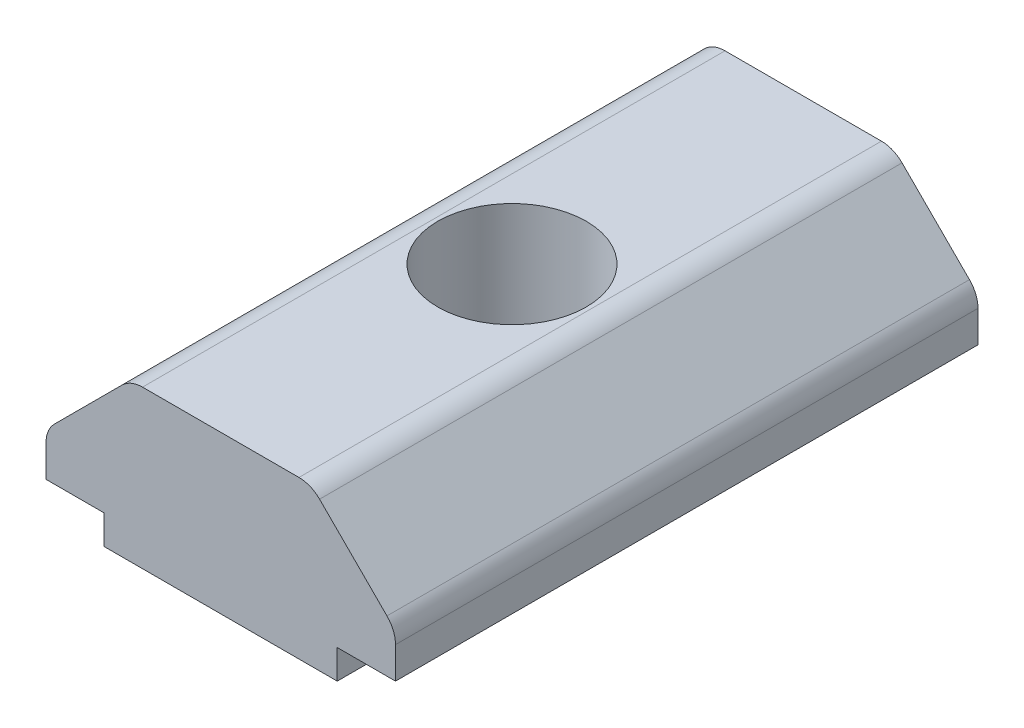
SolidWorks part; units mm, degrees
ref_plane "Front Plane" through (0, 0, 0) normal (0, 0, 1) x (1, 0, 0)
ref_plane "Top Plane" through (0, 0, 0) normal (0, 1, 0) x (1, 0, 0)
ref_plane "Right Plane" through (0, 0, 0) normal (1, 0, 0) x (0, 0, -1)
sketch "Sketch1" plane through (0, 0, 0) normal (0, 0, 1) x (1, 0, 0)
  line L0 (0, 0) -> (8, 0)
  line L1 (8, 0) -> (8, 1)
  line L2 (8, 1) -> (10, 1)
  line L3 (10, 1) -> (10, 2.5)
  line L4 (10, 2.5) -> (7.1, 5.4)
  line L5 (7.1, 5.4) -> (0.9, 5.4)
  line L6 (0.9, 5.4) -> (-2, 2.5)
  line L7 (-2, 2.5) -> (-2, 1)
  line L8 (-2, 1) -> (0, 1)
  line L9 (0, 1) -> (0, 0)
  line L10 (4, 5.4) -> (4, 0) construction
  dimension "D1" = 8
  dimension "D2" = 12
  dimension "D3" = 5.4
  dimension "D4" = 1
  dimension "D5" = 1.5
extrude "Extrude1" add sketch "Sketch1" along normal blind 20
fillet "Fillet1" radius 1 4 edges at (-2, 2.5, 10) (10, 2.5, 10) (0.9, 5.4, 10) (7.1, 5.4, 10)
sketch "Sketch2" plane through (0, 5.4, 0) normal (0, 1, 0) x (1, 0, 0)
  line L0 (4, -20) -> (4, 0) construction
  line L1 (6.6858, -20) -> (1.3142, -20) construction
  line L2 (6.6858, 0) -> (1.3142, 0) construction
  circle A0 centre (4, -10) radius 2.55
  dimension "D1" = 5.1
extrude "Extrude2" cut sketch "Sketch2" against normal through all
sketch "Sketch3" [suppressed] plane through (0, 5.4, 0) normal (0, 1, 0) x (1, 0, 0)
  line L0 (1.3142, -10) -> (6.6858, -10) construction
  line L1 (1.3142, 0) -> (1.3142, -20) construction
  line L2 (6.6858, -20) -> (6.6858, 0) construction
  line L3 (4, -15) -> (4, -10) construction
  circle A0 centre (4, -15) radius 3
  circle A1 centre (4, -5) radius 3
  dimension "D1" = 6
  dimension "D2" = 10
extrude "Extrude3" [suppressed] cut sketch "Sketch3" against normal through all
hole_wizard "M6 Clearance Hole1" [suppressed] positions "3DSketch1" profile "Sketch4" hole size "M6" standard "DIN"
sketch3d "3DSketch1"
  line L0 (4, 0, 20) -> (4, 0, 0) construction
  line L1 (0, 0, 20) -> (8, 0, 20) construction
  line L2 (0, 0, 0) -> (8, 0, 0) construction
  point P0 (4, 0, 10)
sketch "Sketch4" plane through (4, 0, 10) normal (1, 0, 0) x (0, 0, -1)
  line L0 (0, 0) -> (0, 5.4)
  line L1 (0, 5.4) -> (3.3, 5.4)
  line L2 (3.3, 5.4) -> (3.3, 0)
  line L5 (3.3, 0) -> (0, 0)
  line L11 (0, -6.35) -> (0, 107.95) construction
  dimension "Thru Hole Dia." = 6.6
  dimension "Thru Hole Depth" = 5.4
